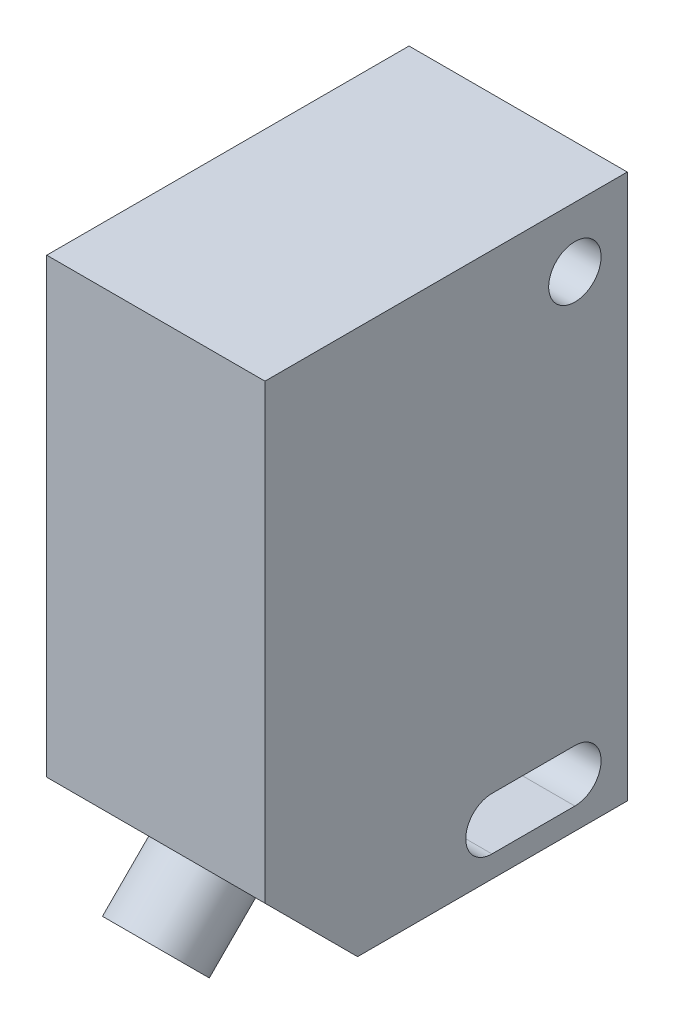
SolidWorks part; units mm, degrees
material "6061-T6 (SS)"
ref_plane "Front Plane" through (0, 0, 0) normal (0, 0, 1) x (1, 0, 0)
ref_plane "Top Plane" through (0, 0, 0) normal (0, 1, 0) x (1, 0, 0)
ref_plane "Right Plane" through (0, 0, 0) normal (1, 0, 0) x (0, 0, -1)
sketch "Sketch1" plane through (0, 0, 0) normal (1, 0, 0) x (0, 0, -1)
  line L0 (-21.082, 5.3882) -> (-15.6938, 0)
  line L1 (-15.6938, 0) -> (0, 0)
  line L2 (-21.082, 5.3882) -> (-21.082, 31.7)
  line L3 (-21.082, 31.7) -> (0, 31.7)
  line L4 (0, 0) -> (0, 31.7)
  line L5 (-7.874, 2.794) -> (-3.048, 2.794) construction
  line L6 (-7.874, 4.318) -> (-3.048, 4.318)
  line L7 (-7.874, 1.27) -> (-3.048, 1.27)
  circle A0 centre (-3.048, 28.194) radius 1.524
  arc A2 (-7.874, 4.318) -> (-7.874, 1.27) centre (-7.874, 2.794) ccw
  arc A3 (-3.048, 1.27) -> (-3.048, 4.318) centre (-3.048, 2.794) ccw
  point P0 (0, 0)
  point P9 (-5.461, 2.794)
  dimension "D4" = 3.048
  dimension "D9" = 7.62
  dimension "D1" = 31.7
  dimension "D2" = 21.082
  dimension "D3" = 135
  dimension "D5" = 4.826
  dimension "D6" = 3.048
  dimension "D7" = 25.4
  dimension "D8" = 2.794
extrude "Boss-Extrude1" add sketch "Sketch1" along normal blind 12.7
sketch "Sketch2" plane through (0, 0, 0) normal (0, 0, 1) x (1, 0, 0)
  line L0 (6.35, 17.85) -> (6.35, 13.85) construction
  line L1 (12.7, 17.85) -> (12.7, 13.85) construction
  line L2 (0, 17.85) -> (0, 13.85) construction
  line L3 (0, 31.7) -> (0, 5.3882) construction
  line L4 (12.7, 31.7) -> (0, 31.7) construction
  line L5 (0, 0) -> (0, 31.7) construction
  arc A0 (12.7, 17.85) -> (0, 17.85) centre (6.35, 17.85) ccw construction
  arc A1 (0, 13.85) -> (12.7, 13.85) centre (6.35, 13.85) ccw construction
  point P2 (6.35, 15.85)
  point P13 (6.35, 31.7)
  point P17 (0, 15.85)
  dimension "D1" = 4
sketch "Sketch3" plane through (0, -7.8469, 7.8469) normal (0, -0.7071, 0.7071) x (1, 0, 0)
  line L0 (0, 14.9072) -> (6.35, 14.9072) construction
  line L2 (0, 18.7172) -> (0, 11.0972) construction
  line L3 (6.35, 14.9072) -> (12.7, 14.9072) construction
  line L5 (12.7, 18.7172) -> (12.7, 11.0972) construction
  circle A0 centre (6.35, 14.9072) radius 2.54
  dimension "D1" = 5.08
extrude "Boss-Extrude2" add sketch "Sketch3" along normal blind 3.81
